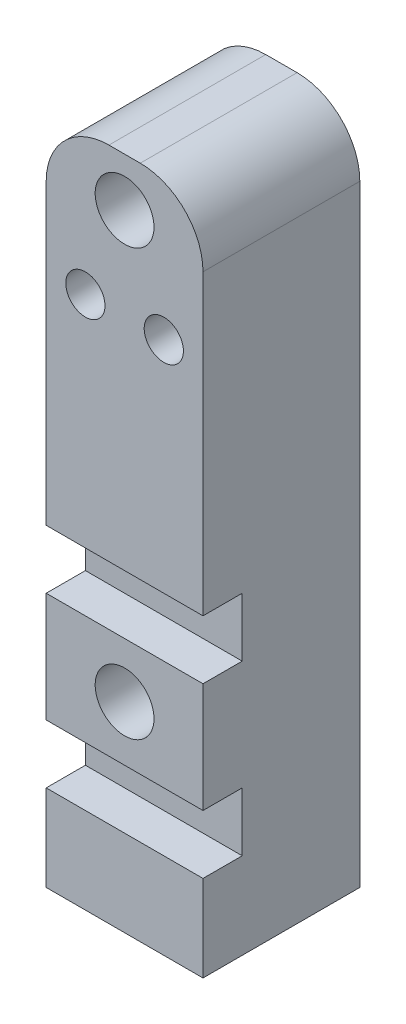
SolidWorks part; units mm, degrees
ref_plane "Front Plane" through (0, 0, 0) normal (0, 0, 1) x (1, 0, 0)
ref_plane "Top Plane" through (0, 0, 0) normal (0, 1, 0) x (1, 0, 0)
ref_plane "Right Plane" through (0, 0, 0) normal (1, 0, 0) x (0, 0, -1)
sketch "Sketch1" plane through (0, 0, 0) normal (0, 1, 0) x (1, 0, 0)
  line L1 (-0.5, 0.5) -> (0.5, 0.5)
  line L2 (-0.5, 0.5) -> (-0.5, -0.5)
  line L3 (-0.5, -0.5) -> (0.5, -0.5)
  line L4 (0.5, 0.5) -> (0.5, -0.5)
  line L5 (-0.5, 0.5) -> (0.5, -0.5) construction
  line L6 (-0.5, -0.5) -> (0.5, 0.5) construction
  point P0 (0, 0)
  dimension "D1" = 1
  dimension "D2" = 1
extrude "Boss-Extrude1" add sketch "Sketch1" along normal blind 4.3
fillet "Fillet1" radius 0.4 1 edges at (0.5, 4.3, 0)
fillet "Fillet2" radius 0.4 1 edges at (-0.5, 4.3, 0)
sketch "Sketch2" plane through (0, 0, 0) normal (0, 1, 0) x (1, 0, 0)
  circle A0 centre (0, 0) radius 0.1
  dimension "D1" = 0.2
extrude "Cut-Extrude1" cut sketch "Sketch2" along normal blind 0.7
ref_plane "Plane2" through (0, 0, 0.5) normal (0, 0, 1) x (1, 0, 0)
sketch "Sketch6" plane through (0, 0, 0.5) normal (0, 0, 1) x (1, 0, 0)
  line L0 (0, 0) -> (0, 0.55) construction
  line L1 (-0.5, 0.55) -> (0.5, 0.55)
  line L2 (0.5, 3.9) -> (0.5, 0) construction
  line L3 (0, 0.55) -> (0, 0.925) construction
  line L4 (-0.5, 0.925) -> (0.5, 0.925)
  line L5 (-0.5, 3.9) -> (-0.5, 0) construction
  line L6 (0.5, 3.9) -> (0.5, 0)
  line L7 (-0.5, 3.9) -> (-0.5, 0)
  line L8 (-0.5, 0.925) -> (-0.5, 0.55)
  line L9 (0.5, 0.925) -> (0.5, 0.55)
  point P8 (0, 0.55)
  point P12 (0, 0.925)
  dimension "D1" = 0.55
  dimension "D2" = 0.375
extrude "Cut-Extrude2" cut sketch "Sketch6" against normal blind 0.25 contours L4 L7 L1 L6
sketch "Sketch8" plane through (0, 0, 0.5) normal (0, 0, 1) x (1, 0, 0)
  line L0 (0, 0.925) -> (0, 1.625) construction
  line L1 (-0.5, 0.925) -> (0.5, 0.925) construction
  line L2 (-0.5, 1.625) -> (0.5, 1.625)
  line L3 (0.5, 3.9) -> (0.5, 0.925) construction
  line L4 (0, 1.625) -> (0, 2) construction
  line L5 (-0.5, 2) -> (0.5, 2)
  line L6 (0.5, 2) -> (0.5, 1.625)
  line L7 (-0.5, 1.625) -> (-0.5, 2)
  point P10 (0, 1.625)
  point P14 (0, 2)
  dimension "D1" = 0.7
  dimension "D2" = 0.375
extrude "Cut-Extrude3" cut sketch "Sketch8" against normal blind 0.25
sketch "Sketch9" plane through (0, 0, 0.5) normal (0, 0, 1) x (1, 0, 0)
  line L0 (0, 0.925) -> (0, 1.625) construction
  line L1 (-0.5, 0.925) -> (0.5, 0.925) construction
  line L2 (-0.5, 1.625) -> (0.5, 1.625) construction
  circle A0 centre (0, 1.275) radius 0.1875
  dimension "D1" = 0.375
extrude "Cut-Extrude4" cut sketch "Sketch9" against normal blind 1
sketch "Sketch10" plane through (0, 0, 0.5) normal (0, 0, 1) x (1, 0, 0)
  line L0 (0, 4.3) -> (0, 3.99) construction
  line L1 (-0.1, 4.3) -> (0.1, 4.3) construction
  circle A0 centre (0, 3.99) radius 0.1875
  dimension "D2" = 0.375
  dimension "D1" = 0.31
extrude "Cut-Extrude5" cut sketch "Sketch10" against normal blind 0.65
sketch "Sketch11" plane through (0, 0, 0.5) normal (0, 0, 1) x (1, 0, 0)
  line L0 (0, 4.3) -> (0, 3.4) construction
  line L1 (-0.1, 4.3) -> (0.1, 4.3) construction
  line L2 (0, 3.4) -> (0.5, 3.4) construction
  line L3 (0.5, 3.9) -> (0.5, 2) construction
  line L4 (0, 3.4) -> (-0.5, 3.4) construction
  line L5 (-0.5, 3.9) -> (-0.5, 2) construction
  line L6 (0.5, 3.4) -> (0.25, 3.4) construction
  circle A0 centre (0.25, 3.4) radius 0.125
  circle A1 centre (-0.25, 3.4) radius 0.125
  dimension "D2" = 0.25
  dimension "D3" = 0.25
  dimension "D1" = 0.9
extrude "Cut-Extrude6" cut sketch "Sketch11" against normal blind 1
sketch "Sketch12" plane through (0, 0, 0.5) normal (0, 0, 1) x (1, 0, 0)
